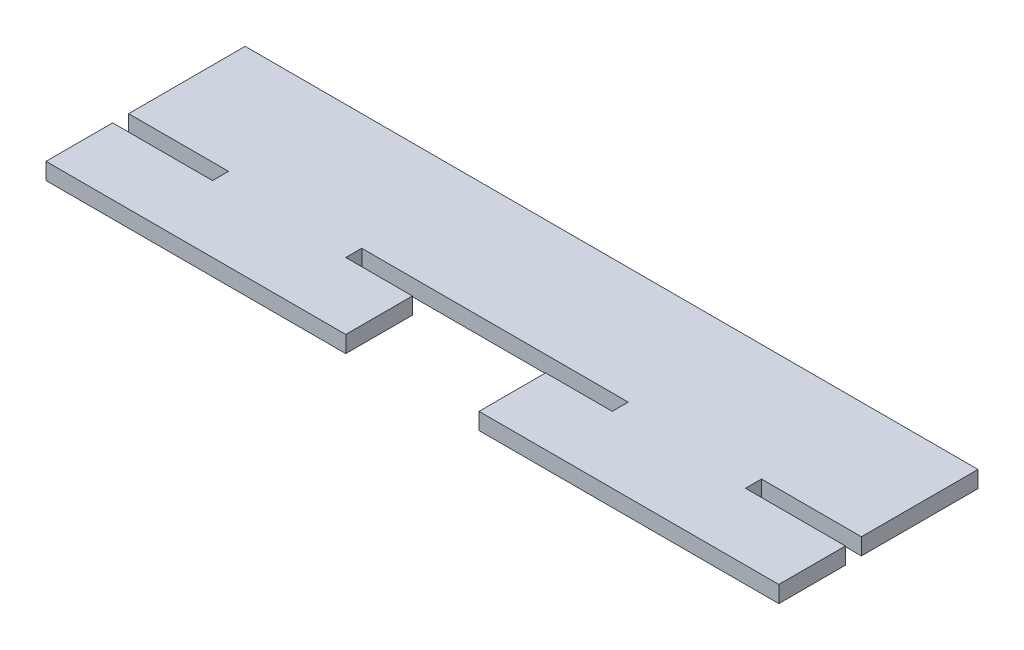
SolidWorks part; units mm, degrees
ref_plane "Front Plane" through (0, 0, 0) normal (0, 0, 1) x (1, 0, 0)
ref_plane "Top Plane" through (0, 0, 0) normal (0, 1, 0) x (1, 0, 0)
ref_plane "Right Plane" through (0, 0, 0) normal (1, 0, 0) x (0, 0, -1)
sketch "Sketch1" plane through (0, 0, 0) normal (0, 1, 0) x (1, 0, 0)
  line L0 (-69.85, 22.225) -> (69.85, 22.225)
  line L1 (0, 0) -> (0, 36230.2906) construction
  line L2 (-25.4, 0) -> (25.4, 0)
  line L3 (25.4, 0) -> (25.4, -3.048)
  line L4 (25.4, -3.048) -> (50.8, -3.048) construction
  line L5 (50.8, -3.048) -> (50.8, 0)
  line L6 (50.8, 0) -> (69.85, 0)
  line L7 (69.85, 0) -> (69.85, 22.225)
  line L8 (-25.4, 0) -> (-25.4, -3.048)
  line L9 (-25.4, -3.048) -> (-50.8, -3.048) construction
  line L10 (-50.8, -3.048) -> (-50.8, 0)
  line L11 (-50.8, 0) -> (-69.85, 0)
  line L12 (-69.85, 0) -> (-69.85, 22.225)
  line L13 (-50.8, -3.048) -> (-69.85, -3.048)
  line L14 (-69.85, -3.048) -> (-69.85, -15.748)
  line L15 (-69.85, -15.748) -> (-12.7, -15.748)
  line L16 (-12.7, -15.748) -> (-12.7, -3.048)
  line L17 (-12.7, -3.048) -> (-25.4, -3.048)
  line L18 (25.4, -3.048) -> (12.7, -3.048)
  line L19 (12.7, -3.048) -> (12.7, -15.748)
  line L20 (12.7, -15.748) -> (69.85, -15.748)
  line L21 (69.85, -15.748) -> (69.85, -3.048)
  line L22 (69.85, -3.048) -> (50.8, -3.048)
  point P5 (0, 22.225)
  dimension "D1" = 22.225
  dimension "D2" = 139.7
  dimension "D3" = 50.8
  dimension "D4" = 25.4
  dimension "D5" = 3.048
  dimension "D6" = 25.4
  dimension "D7" = 12.7
extrude "Boss-Extrude1" add sketch "Sketch1" along normal blind 3.175
